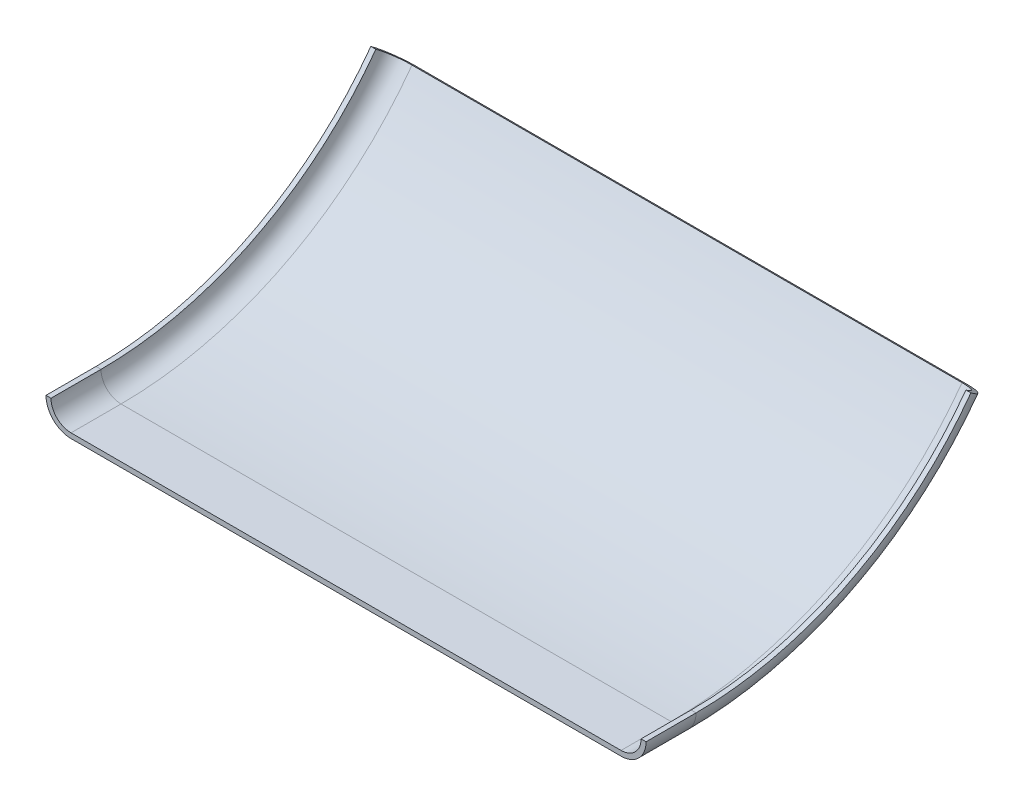
SolidWorks part; units mm, degrees
ref_plane "Front Plane" through (0, 0, 0) normal (0, 0, 1) x (1, 0, 0)
ref_plane "Top Plane" through (0, 0, 0) normal (0, 1, 0) x (1, 0, 0)
ref_plane "Right Plane" through (0, 0, 0) normal (1, 0, 0) x (0, 0, -1)
sketch "Sketch1" plane through (0, 0, 0) normal (0, 0, 1) x (1, 0, 0)
  line L0 (-139.7, 0) -> (139.7, 0)
  line L1 (139.7, 0) -> (152.4, 0) construction
  line L2 (152.4, 0) -> (152.4, 12.7) construction
  line L3 (0, 19.8378) -> (0, -30.07) construction
  line L4 (0, 0) -> (0, 2.54)
  line L5 (-139.7, 2.54) -> (139.7, 2.54)
  line L6 (152.4, 12.7) -> (149.86, 12.7)
  line L7 (-152.4, 12.7) -> (-149.86, 12.7)
  arc A0 (139.7, 0) -> (152.4, 12.7) centre (139.7, 12.7) ccw
  arc A1 (-139.7, 0) -> (-152.4, 12.7) centre (-139.7, 12.7) cw
  arc A2 (139.7, 2.54) -> (149.86, 12.7) centre (139.7, 12.7) ccw
  arc A3 (-139.7, 2.54) -> (-149.86, 12.7) centre (-139.7, 12.7) cw
  point P11 (0, 0)
  dimension "D1" = 139.7
  dimension "D2" = 12.7
  dimension "D3" = 12.7
  dimension "D4" = 2.54
sketch "Sketch2" plane through (0, 0, 0) normal (1, 0, 0) x (0, 0, -1)
  line L0 (0, 0) -> (175.26, 0) construction
  line L1 (175.26, 0) -> (175.26, 76.2) construction
  line L2 (0, 0) -> (25.4, 0)
  arc A0 (25.4, 0) -> (175.26, 76.2) centre (25.4, 185.4623) ccw
  dimension "D3" = 25.4
  dimension "D1" = 175.26
  dimension "D2" = 76.2
sweep "Sweep1" add profiles "Sketch1" path "Sketch2"
